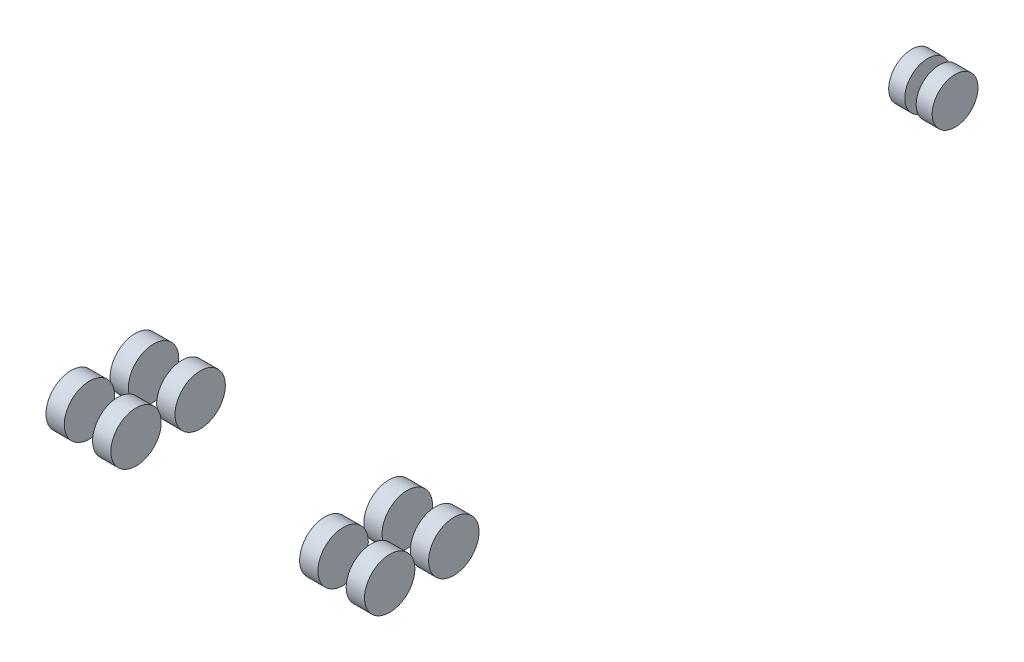
SolidWorks part; units mm, degrees
ref_plane "Front Plane" through (0, 0, 0) normal (0, 0, 1) x (1, 0, 0)
ref_plane "Top Plane" through (0, 0, 0) normal (0, 1, 0) x (1, 0, 0)
ref_plane "Right Plane" through (0, 0, 0) normal (1, 0, 0) x (0, 0, -1)
sketch "Height to CG" plane through (0, 0, 0) normal (0, 0, 1) x (1, 0, 0)
  line L0 (0, 0) -> (0, 3352.8)
  line L1 (0, 0) -> (2813.3332, 0)
  line L2 (2813.3332, 0) -> (0, 3352.8)
  dimension "D1" = 3352.8
  dimension "D2" = 50
sketch "Max bottom" plane through (0, 0, 0) normal (0, 1, 0) x (1, 0, 0)
  line L0 (0, 12192) -> (2813.3332, -2689.5552)
  line L1 (2813.3332, -2689.5552) -> (-2813.3332, -2689.5552)
  line L2 (-2813.3332, -2689.5552) -> (0, 12192)
  line L3 (0, 12192) -> (0, -2689.5552)
  line L4 (-2296.6162, -2689.5552) -> (-2296.6162, 43.6984)
  line L5 (-2813.3332, -2689.5552) -> (-3330.0503, -2689.5552)
  line L6 (2813.3332, -2689.5552) -> (3330.0503, -2689.5552)
  line L7 (-304.8, -2689.5552) -> (-304.8, 12192)
  line L8 (304.8, -2689.5552) -> (304.8, 12192)
  point P4 (0, -2689.5552)
  point P8 (2296.6162, -2689.5552)
  point P15 (0, 0)
  point P16 (0, 0)
  point P17 (0, 0)
  point P18 (0, 0)
  dimension "D1" = 5626.6665
  dimension "D2" = 2689.5552
  dimension "D3" = 12192
  dimension "D4" = 516.717
  dimension "D5" = 516.717
  dimension "D6" = 516.717
  dimension "D7" = 516.717
  dimension "D8" = 304.8
  dimension "D9" = 304.8
ref_plane "Plane1" through (-2813.3332, 0, 0) normal (1, 0, 0) x (0, 0, -1)
ref_plane "Plane2" through (2813.3332, 0, 0) normal (1, 0, 0) x (0, 0, -1)
ref_plane "Plane3" through (-2296.6162, 0, 0) normal (1, 0, 0) x (0, 0, -1)
sketch "Sketch9" plane through (-2296.6162, 0, 0) normal (1, 0, 0) x (0, 0, -1)
  line L0 (-3400.7552, 558.8) -> (-1978.3552, 558.8) construction
  line L1 (-2689.5552, 0) -> (-2689.5552, 558.8) construction
  line L2 (-2689.5552, 0) -> (43.6984, 0) construction
  circle A0 centre (-3400.7552, 558.8) radius 558.8
  circle A1 centre (-1978.3552, 558.8) radius 558.8
  point P8 (0, 0)
  point P9 (-2689.5552, 558.8)
  point P10 (-2677.8387, 0)
  point P11 (-2847.1271, 0)
  dimension "D2" = 1117.6
  dimension "D3" = 1117.6
  dimension "D1" = 1422.4
extrude "Main tire 1" add sketch "Sketch9" along normal blind 203.2 and the other way blind 203.2
ref_plane "Plane4" through (-3330.0503, 0, 0) normal (1, 0, 0) x (0, 0, -1)
sketch "Sketch10" plane through (-3330.0503, 0, 0) normal (1, 0, 0) x (0, 0, -1)
  circle A0 centre (-3400.7552, 558.8) radius 558.8
  circle A1 centre (-1978.3552, 558.8) radius 558.8
  dimension "D2" = 1117.6
  dimension "D1" = 1117.6
extrude "Main tire 2" add sketch "Sketch10" along normal blind 203.2 and the other way blind 203.2 separate body
ref_plane "Plane5" through (2296.6162, 0, 0) normal (1, 0, 0) x (0, 0, -1)
ref_plane "Plane6" through (3330.0503, 0, 0) normal (1, 0, 0) x (0, 0, -1)
sketch "Sketch12" plane through (2296.6162, 0, 0) normal (1, 0, 0) x (0, 0, -1)
  circle A0 centre (-1978.3552, 558.8) radius 558.8
  circle A1 centre (-3400.7552, 558.8) radius 558.8
  dimension "D2" = 1117.6
  dimension "D1" = 1117.6
extrude "Main tire 3" add sketch "Sketch12" along normal blind 203.2 and the other way blind 203.2 separate body
sketch "Sketch13" plane through (3330.0503, 0, 0) normal (1, 0, 0) x (0, 0, -1)
  circle A0 centre (-3400.7552, 558.8) radius 558.8
  circle A1 centre (-1978.3552, 558.8) radius 558.8
  dimension "D2" = 1117.6
  dimension "D1" = 1117.6
extrude "Main tire 4" add sketch "Sketch13" along normal blind 203.2 and the other way blind 203.2 separate body
ref_plane "Plane7" through (-304.8, 0, 0) normal (1, 0, 0) x (0, 0, -1)
ref_plane "Plane8" through (304.8, 0, 0) normal (1, 0, 0) x (0, 0, -1)
sketch "Sketch14" plane through (-304.8, 0, 0) normal (1, 0, 0) x (0, 0, -1)
  line L0 (12192, 0) -> (12192, 508) construction
  line L1 (-2689.5552, 0) -> (12192, 0) construction
  circle A0 centre (12192, 508) radius 508
  point P5 (11712.6396, 1514.7626)
  point P6 (0, 0)
  dimension "D1" = 1016
extrude "Nose tire 1" add sketch "Sketch14" along normal blind 177.8 and the other way blind 177.8 separate body
sketch "Sketch15" plane through (304.8, 0, 0) normal (1, 0, 0) x (0, 0, -1)
  circle A0 centre (12192, 508) radius 508
  dimension "D1" = 1016
extrude "Nose tire 2" add sketch "Sketch15" along normal blind 177.8 and the other way blind 177.8 separate body
equation "\"D1@Height to CG\" = \"z\""
equation "\"z\" = 11'input from front view aircraft, 5 degree clearance"
equation "\"angle\"= 50'maximum 63 degree"
equation "\"D2@Height to CG\" = \"angle\""
equation "\"D1@Max bottom\" = \"z\" / tan ( \"angle\" )  * 2"
equation "\"Main tire diameter\" = 44 / 12"
equation "\"Main tire length\" = 16 / 12"
equation "\"D4@Max bottom\"=(tan( 36) * (\"Main tire diameter\"+1) ) * 0.5"
equation "\"D1@Sketch9\"=\"Main tire diameter\"+1"
equation "\"D2@Sketch9\"=\"Main tire diameter\""
equation "\"D3@Sketch9\"=\"Main tire diameter\""
equation "\"D1@Main tire 1\"=\"Main tire length\"*0.5"
equation "\"D2@Main tire 1\"=\"Main tire length\"*0.5"
equation "\"D5@Max bottom\"=\"D4@Max bottom\""
equation "\"D1@Main tire 2\"=\"Main tire length\"*0.5"
equation "\"D2@Main tire 2\"=\"Main tire length\"*0.5"
equation "\"D6@Max bottom\"=\"D4@Max bottom\""
equation "\"D7@Max bottom\"=\"D4@Max bottom\""
equation "\"D1@Sketch10\"=\"Main tire diameter\""
equation "\"D2@Sketch10\"=\"Main tire diameter\""
equation "\"D1@Sketch12\"=\"Main tire diameter\""
equation "\"D2@Sketch12\"=\"Main tire diameter\""
equation "\"D1@Main tire 3\"=\"Main tire length\"*0.5"
equation "\"D2@Main tire 3\"=\"Main tire length\"*0.5"
equation "\"D1@Sketch13\"=\"Main tire diameter\""
equation "\"D2@Sketch13\"=\"Main tire diameter\""
equation "\"D1@Main tire 4\"=\"Main tire length\"*0.5"
equation "\"D2@Main tire 4\"=\"Main tire length\"*0.5"
equation "\"Nose tire diameter\" = 40 / 12"
equation "\"Nose tire length\"= 14 / 12"
equation "\"D1@Sketch14\"=\"Nose tire diameter\""
equation "\"D1@Nose tire 1\"=\"Nose tire length\"*0.5"
equation "\"D2@Nose tire 1\"=\"Nose tire length\"*0.5"
equation "\"D9@Max bottom\"=(10/12+\"Nose tire length\")*0.5"
equation "\"D8@Max bottom\"=(10/12+\"Nose tire length\")*0.5"
equation "\"D1@Sketch15\"=\"Nose tire diameter\""
equation "\"D1@Nose tire 2\"=\"Nose tire length\"*0.5"
equation "\"D2@Nose tire 2\"=\"Nose tire length\"*0.5"
